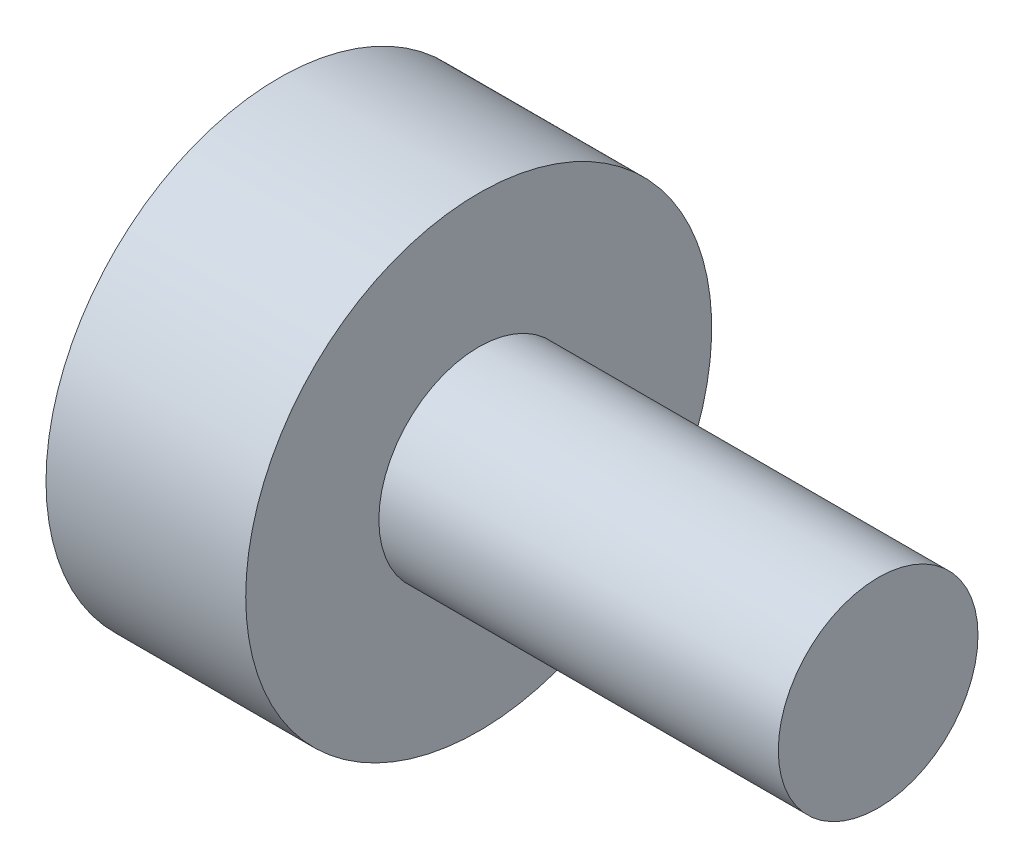
SolidWorks part; units mm, degrees
ref_plane "Спереди" through (0, 0, 0) normal (0, 0, 1) x (1, 0, 0)
ref_plane "Сверху" through (0, 0, 0) normal (0, 1, 0) x (1, 0, 0)
ref_plane "Справа" through (0, 0, 0) normal (1, 0, 0) x (0, 0, -1)
sketch "Эскиз1" plane through (0, 0, 0) normal (0, 0, 1) x (1, 0, 0)
  line L0 (0, 0) -> (100, 0)
  line L1 (0, 0) -> (0, 20)
  line L2 (0, 20) -> (10, 20)
  line L3 (10, 20) -> (10, 35)
  line L4 (10, 35) -> (40, 35)
  line L5 (40, 35) -> (40, 15)
  line L6 (40, 15) -> (100, 15)
  line L7 (100, 0) -> (100, 15)
revolve "Повернуть1" add sketch "Эскиз1" angle 360 about L0
sketch "Эскиз2" plane through (0, 0, 0) normal (0, 0, 1) x (1, 0, 0)
  circle A0 centre (0, 0) radius 5
extrude "Вырез-Вытянуть1" cut sketch "Эскиз2" against normal blind 20
